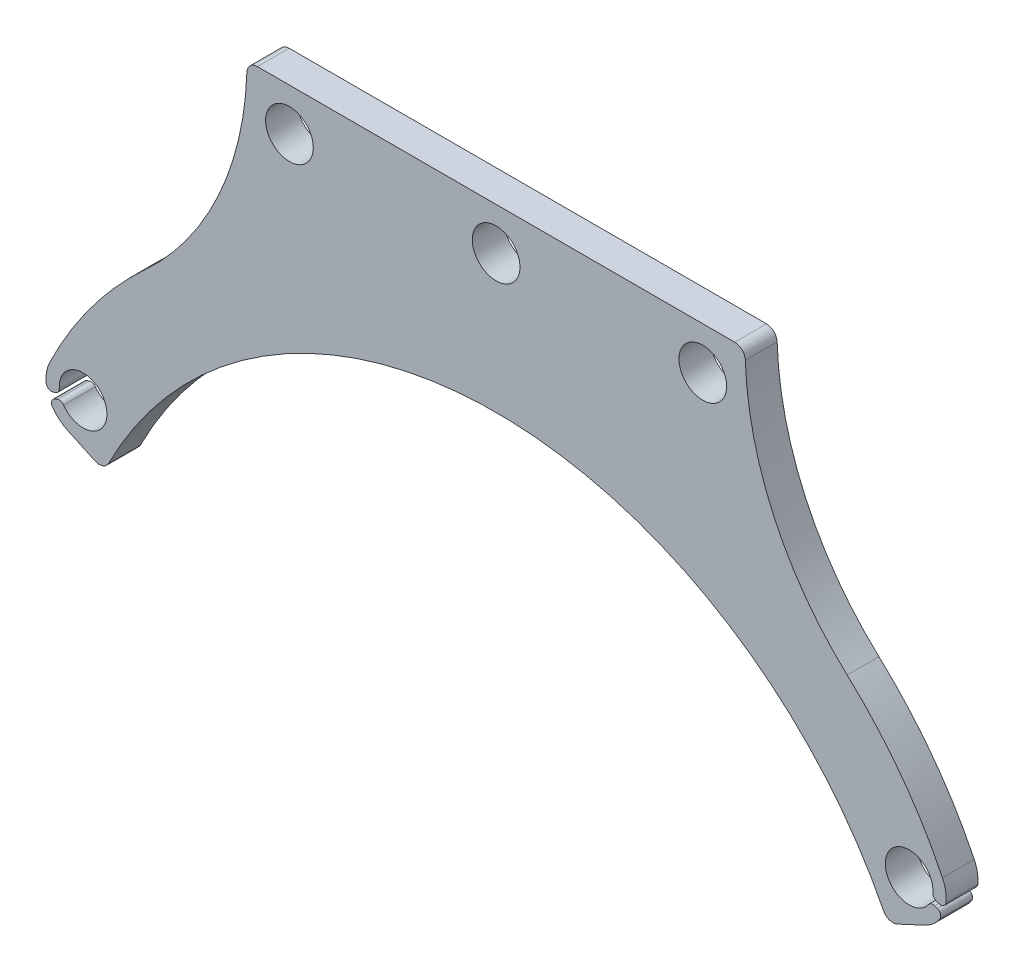
SolidWorks part; units mm, degrees
ref_plane "前视基准面" through (0, 0, 0) normal (0, 0, 1) x (1, 0, 0)
ref_plane "上视基准面" through (0, 0, 0) normal (0, 1, 0) x (1, 0, 0)
ref_plane "右视基准面" through (0, 0, 0) normal (1, 0, 0) x (0, 0, -1)
ref_plane "基准面1" through (0, 0, 0) normal (0, 0, -1) x (-1, 0, 0)
sketch "草图1" plane through (0, 0, 0) normal (0, 0, -1) x (-1, 0, 0)
  line L0 (-41.792, -38.2369) -> (-41.5479, -38.1502)
  line L1 (-41.3805, -38.6213) -> (-41.6246, -38.7081)
  line L2 (-40.4503, -40.6721) -> (-37.8648, -41.8777)
  line L3 (37.8648, -41.8777) -> (40.4503, -40.6721)
  line L4 (41.6246, -38.7081) -> (41.3805, -38.6213)
  line L5 (41.5479, -38.1502) -> (41.792, -38.2369)
  line L6 (22.5163, -2) -> (-22.5163, -2)
  circle A0 centre (0, -6) radius 2.25
  circle A1 centre (19.5, -6) radius 2.25
  circle A2 centre (-19.5, -6) radius 2.25
  arc A3 (-33.1254, -23.8931) -> (-42.1201, -35.9723) centre (-5.9406, -53.5247) ccw
  arc A4 (-42.1201, -35.9723) -> (-42.4574, -37.8101) centre (-38.9711, -37.5) ccw
  arc A5 (-42.4574, -37.8101) -> (-41.792, -38.2369) centre (-41.9593, -37.7658) ccw
  arc A6 (-41.5479, -38.1502) -> (-41.2164, -37.6465) centre (-41.7153, -37.6791) ccw
  arc A7 (-41.2164, -37.6465) -> (-40.8055, -38.8029) centre (-38.9711, -37.5) cw
  arc A8 (-40.8055, -38.8029) -> (-41.3805, -38.6213) centre (-41.2131, -39.0925) ccw
  arc A9 (-41.6246, -38.7081) -> (-41.8715, -39.4591) centre (-41.4572, -39.1792) ccw
  arc A10 (-41.8715, -39.4591) -> (-40.4503, -40.6721) centre (-38.9711, -37.5) ccw
  arc A11 (-37.8648, -41.8777) -> (-36.5507, -41.4245) centre (-37.4421, -40.9714) ccw
  arc A12 (-36.5507, -41.4245) -> (36.5507, -41.4245) centre (0, -60) cw
  arc A13 (36.5507, -41.4245) -> (37.8648, -41.8777) centre (37.4421, -40.9714) ccw
  arc A14 (40.4503, -40.6721) -> (41.8715, -39.4591) centre (38.9711, -37.5) ccw
  arc A15 (41.8715, -39.4591) -> (41.6246, -38.7081) centre (41.4572, -39.1792) ccw
  arc A16 (41.3805, -38.6213) -> (40.8055, -38.8029) centre (41.2131, -39.0925) ccw
  arc A17 (40.8055, -38.8029) -> (41.2164, -37.6465) centre (38.9711, -37.5) cw
  arc A18 (41.2164, -37.6465) -> (41.5479, -38.1502) centre (41.7153, -37.6791) ccw
  arc A19 (41.792, -38.2369) -> (42.4574, -37.8101) centre (41.9593, -37.7658) ccw
  arc A20 (42.4574, -37.8101) -> (42.1201, -35.9723) centre (38.9711, -37.5) ccw
  arc A21 (42.1201, -35.9723) -> (33.1254, -23.8931) centre (5.9406, -53.5247) ccw
  arc A22 (33.1254, -23.8931) -> (23.5158, -2.9674) centre (53.2108, -2) cw
  arc A23 (23.5158, -2.9674) -> (22.5163, -2) centre (22.5163, -3) ccw
  arc A24 (-22.5163, -2) -> (-23.5158, -2.9674) centre (-22.5163, -3) ccw
  arc A25 (-23.5158, -2.9674) -> (-33.1254, -23.8931) centre (-53.2108, -2) cw
extrude "凸台-拉伸1" add sketch "草图1" against normal blind 3
